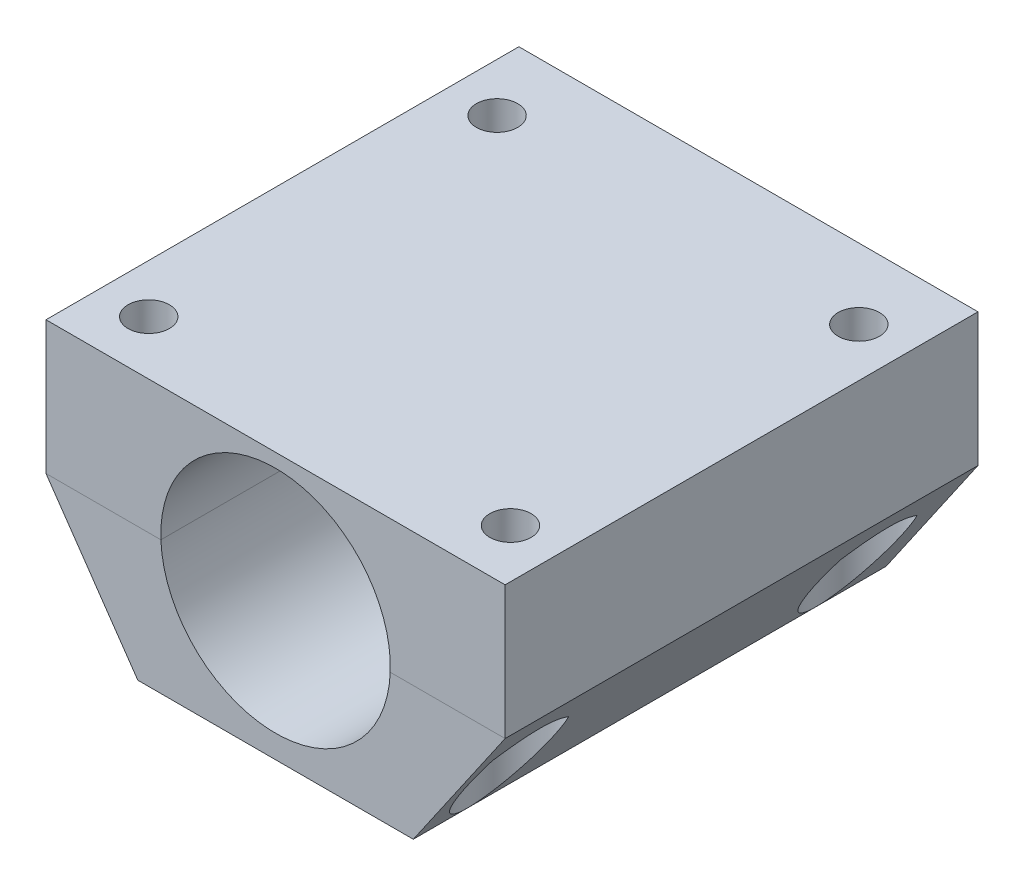
SolidWorks part; units mm, degrees
ref_plane "Plan de face" through (0, 0, 0) normal (0, 0, 1) x (1, 0, 0)
ref_plane "Plan de dessus" through (0, 0, 0) normal (0, 1, 0) x (1, 0, 0)
ref_plane "Plan de droite" through (0, 0, 0) normal (1, 0, 0) x (0, 0, -1)
sketch "Esquisse1" plane through (0, 0, 0) normal (0, 0, 1) x (1, 0, 0)
  line L4 (0, 12.5) -> (0, 14) construction
  line L5 (0, -12.5) -> (0, -15) construction
  line L7 (-15, 14) -> (15, 14)
  line L8 (15, 14) -> (15, -15)
  line L9 (15, -15) -> (-15, -15)
  line L10 (-15, -15) -> (-15, 14)
  line L11 (-15, -0.5) -> (-25, -0.5)
  line L12 (-25, -0.5) -> (-25, 14)
  line L13 (-25, 14) -> (-15, 14)
  line L14 (15, 14) -> (25, 14)
  line L15 (25, 14) -> (25, -0.5)
  line L16 (25, -0.5) -> (15, -0.5)
  line L17 (-25, -0.5) -> (-15, -15)
  line L18 (15, -15) -> (25, -0.5)
  line L19 (25, -0.5) -> (-25, -0.5) construction
  circle A0 centre (0, 0) radius 12.5
  point P9 (0, 14)
  dimension "D1" = 25
  dimension "D2" = 30
  dimension "D3" = 1.5
  dimension "D4" = 2.5
  dimension "D5" = 10
  dimension "D6" = 10
extrude "Boss.-Extru.1" add sketch "Esquisse1" along normal blind 50 contours L13 L12 L11 L10 | L11 L17 L10 | L10 L9 L8 L7 A0 | L8 L18 L16 | L16 L15 L14 L8
ref_plane "Plan1" through (0, -0.5, 0) normal (0, 1, 0) x (1, 0, 0)
hole_wizard "Fraisage pour vis à tête fraisée M41" positions "Esquisse24" profile "Esquisse25" countersink size "M4" standard "ISO" end condition through all
sketch "Esquisse24" plane through (0, -15, 0) normal (0, -1, 0) x (-1, 0, 0)
  point P0 (-19.6987, -6.1768)
  point P2 (19.6987, -6.1768)
  point P4 (19.6987, -44.115)
  point P6 (-19.6987, -44.115)
sketch "Esquisse25" plane through (19.6987, -15, 6.1768) normal (1, 0, 0) x (0, 0, -1)
  line L0 (0, 0) -> (0, 29)
  line L1 (0, 29) -> (2.25, 29)
  line L2 (2.25, 29) -> (2.25, 12.45)
  line L3 (2.25, 12.45) -> (4.7, 10)
  line L4 (4.7, 10) -> (4.7, 0)
  line L6 (4.7, 0) -> (0, 0)
  line L7 (-2.25, 12.45) -> (-4.7, 10) construction
  line L11 (0, -6.35) -> (0, 107.95) construction
  dimension "Diamètre du perçage jusqu'au prochain" = 4.5
  dimension "Profondeur du perçage jusqu'au prochain" = 29
  dimension "Diamètre du fraisage" = 9.4
  dimension "Angle du fraisage" = 90
  dimension "Dégagement de la tête" = 10
sketch "Esquisse26" plane through (0, 0, 0) normal (0, 0, -1) x (-1, 0, 0)
  line L0 (-25, 14) -> (25, 14)
  line L1 (25, 14) -> (25, -0.5)
  line L2 (25, -0.5) -> (15, -15)
  line L3 (15, -15) -> (-15, -15)
  line L4 (-15, -15) -> (-25, -0.5)
  line L5 (-25, -0.5) -> (-25, 14)
  circle A0 centre (0, 0) radius 3.75
  dimension "D1" = 7.5
extrude "Boss.-Extru.2" add sketch "Esquisse26" along normal blind 1.5
hole_wizard "Dégagement M31" positions "Esquisse27" profile "Esquisse28" hole size "M3" standard "ISO" end condition through all
sketch "Esquisse27" plane through (0, 0, -1.5) normal (0, 0, -1) x (-1, 0, 0)
  circle A0 centre (0, 0) radius 3.75 construction
  point P0 (-8.5, 0)
  point P2 (8.5, 0)
  dimension "D1" = 8.5
  dimension "D2" = 8.5
sketch "Esquisse28" plane through (8.5, 0, -1.5) normal (1, 0, 0) x (0, 1, 0)
  line L0 (0, 0) -> (0, 51.5)
  line L1 (0, 51.5) -> (1.7, 51.5)
  line L2 (1.7, 51.5) -> (1.7, 0)
  line L5 (1.7, 0) -> (0, 0)
  line L11 (0, -6.35) -> (0, 107.95) construction
  dimension "Diamètre du perçage jusqu'au prochain" = 3.4
  dimension "Profondeur du perçage jusqu'au prochain" = 51.5
split "Fractionner1" trim tools "Plan1" bodies to split 118 resulting bodies 119 120
